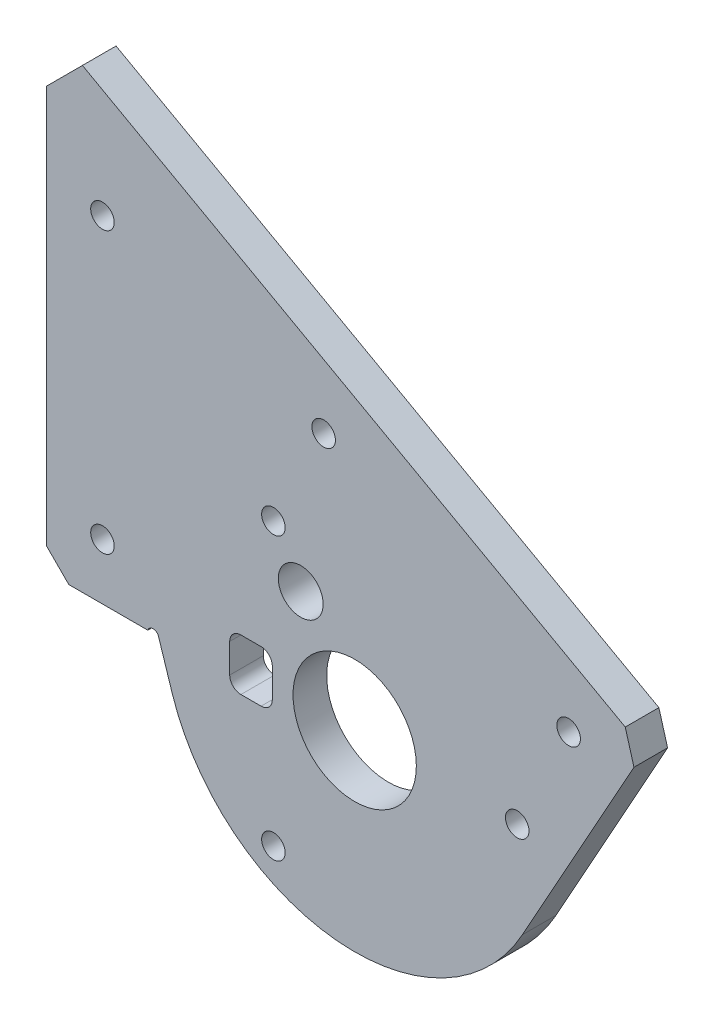
SolidWorks part; units mm, degrees
ref_plane "前视基准面" through (0, 0, 0) normal (0, 0, 1) x (1, 0, 0)
ref_plane "上视基准面" through (0, 0, 0) normal (0, 1, 0) x (1, 0, 0)
ref_plane "右视基准面" through (0, 0, 0) normal (1, 0, 0) x (0, 0, -1)
sketch "草图1" plane through (0, 0, 0) normal (0, 0, 1) x (1, 0, 0)
  line L0 (-55, 82.0337) -> (125, -17.9663) construction
  line L1 (-55, 82.0337) -> (-55, -2.9663)
  line L2 (-14.5, 25.1147) -> (0, 0) construction
  line L3 (-55, -2.9663) -> (-35, -2.9663)
  line L4 (29.9141, -16.6189) -> (51.768, 22.7182)
  line L5 (51.768, 22.7182) -> (-55, 82.0337)
  line L6 (-35, -2.9663) -> (15, -157.9663) construction
  line L7 (-35, -2.9663) -> (-32.5679, -10.5058)
  circle A0 centre (0, 0) radius 29 construction
  circle A2 centre (29, 0) radius 2.1
  circle A3 centre (-14.5, -25.1147) radius 2.1
  circle A4 centre (-14.5, 25.1147) radius 2.1
  circle A5 centre (-9.625, 16.671) radius 4
  circle A6 centre (0, 0) radius 19.25 construction
  arc A9 (-32.5679, -10.5058) -> (29.9141, -16.6189) centre (0, 0) ccw
  circle A10 centre (0, 0) radius 11
  point P14 (0, 0)
  dimension "D3" = 58
  dimension "D4" = 4.2
  dimension "D6" = 38.5
  dimension "D7" = 8
  dimension "D11" = 45
  dimension "D12" = 155
  dimension "D14" = 22
  dimension "D1" = 180
  dimension "D2" = 100
  dimension "D8" = 55
  dimension "D9" = 20
  dimension "D10" = 85
  dimension "D13" = 50
  dimension "D5" = 3
extrude "凸台-拉伸1" add sketch "草图1" along normal mid plane 6
sketch "草图3" plane through (0, 0, 3) normal (0, 0, 1) x (1, 0, 0)
  line L0 (-35, -2.9663) -> (-32.5679, -10.5058) construction
  line L1 (-55, 82.0337) -> (-55, -2.9663) construction
  line L2 (-55, -2.9663) -> (-35, -2.9663) construction
  line L3 (-45, 57.0337) -> (-45, 7.0337) construction
  circle A1 centre (-35.9517, -3.2733) radius 1
  circle A2 centre (-45, 7.0337) radius 2.1
  circle A3 centre (-45, 57.0337) radius 2.1
  circle A4 centre (-14.5, -25.1147) radius 2.1 construction
  dimension "D1" = 2
  dimension "D2" = 10
  dimension "D3" = 10
  dimension "D4" = 50
extrude "切除-拉伸1" cut sketch "草图3" against normal through all
chamfer "倒角2" distance 4 angle 45 2 edges at (51.768, 22.7182, 0) (-55, -2.9663, 0)
chamfer "倒角3" distance 10 angle 45 1 edges at (-55, 82.0337, 0)
sketch "草图4" plane through (0, 0, 3) normal (0, 0, 1) x (1, 0, 0)
  line L0 (0, 0) -> (-18.5, 0) construction
  line L1 (-14.7, 4.6) -> (-22.3, 4.6)
  line L2 (-16.2, -3.1) -> (-20.8, -3.1) construction
  line L3 (-16.2, -3.1) -> (-16.2, 3.1) construction
  line L4 (-16.2, 3.1) -> (-20.8, 3.1) construction
  line L5 (-20.8, -3.1) -> (-20.8, 3.1) construction
  line L6 (-16.2, -3.1) -> (-20.8, 3.1) construction
  line L7 (-16.2, 3.1) -> (-20.8, -3.1) construction
  line L8 (-22.3, -4.6) -> (-22.3, 4.6)
  line L9 (-14.7, -4.6) -> (-22.3, -4.6)
  line L10 (-14.7, -4.6) -> (-14.7, 4.6)
  dimension "D1" = 18.5
  dimension "D2" = 4.6
  dimension "D3" = 6.2
  dimension "D4" = 1.5
extrude "切除-拉伸2" cut sketch "草图4" against normal through all
fillet "圆角1" radius 2 4 edges at (-22.3, -4.6, 0) (-14.7, -4.6, 0) (-22.3, 4.6, 0) (-14.7, 4.6, 0)
sketch "草图5" plane through (0, 0, 3) normal (0, 0, 1) x (1, 0, 0)
  line L0 (48.2714, 24.6607) -> (-48.5714, 78.4623) construction
  line L1 (29.9141, -16.6189) -> (49.8254, 19.2215) construction
  circle A0 centre (-5.5379, 43.1152) radius 2.1
  circle A1 centre (38.17, 18.833) radius 2.1
  dimension "D1" = 10
  dimension "D2" = 10
  dimension "D3" = 10
  dimension "D4" = 50
  dimension "D5" = 4.2
extrude "切除-拉伸3" cut sketch "草图5" against normal through all
chamfer "倒角1" distance 2 angle 45 4 edges at (-42.9, 7.0337, -3) (-42.9, 57.0337, -3) (40.27, 18.833, -3) (-3.4379, 43.1152, -3)
